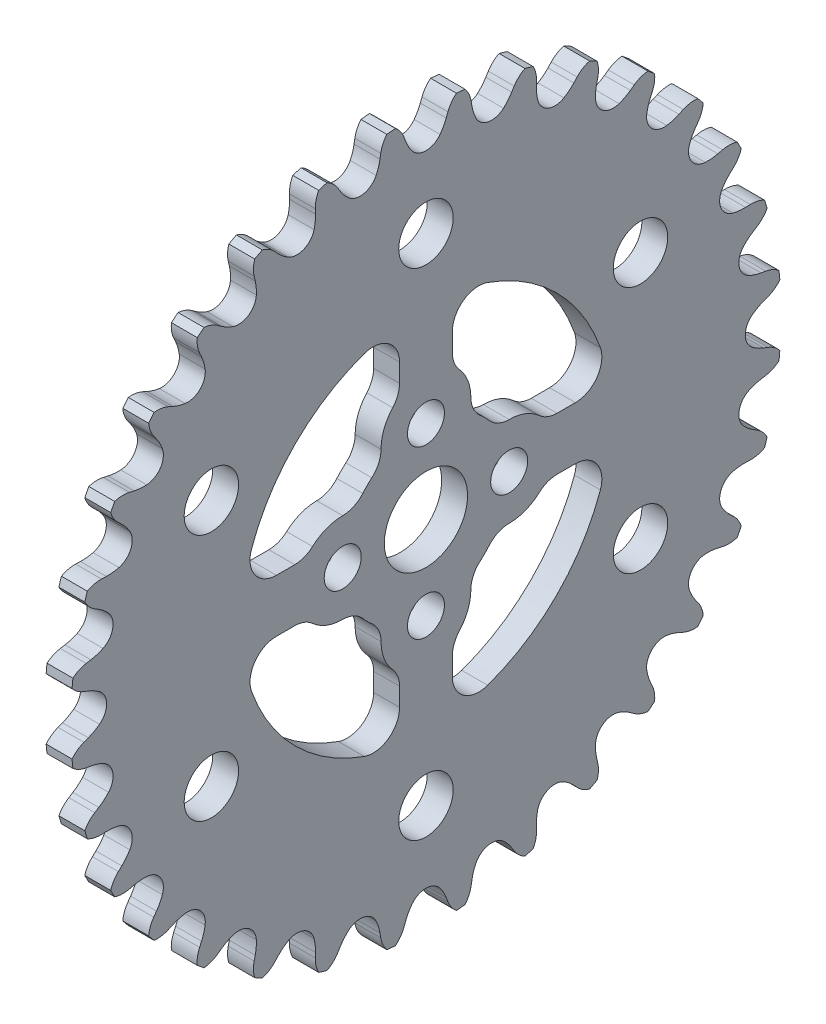
SolidWorks part; units mm, degrees
ref_plane "Front Plane" through (0, 0, 0) normal (0, 0, 1) x (1, 0, 0)
ref_plane "Top Plane" through (0, 0, 0) normal (0, 1, 0) x (1, 0, 0)
ref_plane "Right Plane" through (0, 0, 0) normal (1, 0, 0) x (0, 0, -1)
ref_plane "Plane1" through (2.4892, 0, 0) normal (1, 0, 0) x (0, 0, -1)
sketch "Sketch1" plane through (2.4892, 0, 0) normal (1, 0, 0) x (0, 0, -1)
  line L0 (12.6071, -2.54) -> (14.3684, -2.54)
  line L1 (2.54, -14.3684) -> (2.54, -12.6071)
  line L2 (-14.3684, -2.54) -> (-12.6071, -2.54)
  line L3 (-2.54, -12.6071) -> (-2.54, -14.3684)
  line L4 (-4.3457, 32.6567) -> (-4.4202, 32.2055)
  line L5 (-8.2408, 31.4456) -> (-8.4823, 31.8339)
  line L6 (-10.6332, 31.1814) -> (-10.6183, 30.7244)
  line L7 (-14.2172, 29.2337) -> (-14.5298, 29.5674)
  line L8 (-16.5121, 28.5078) -> (-16.4083, 28.0625)
  line L9 (-19.6472, 25.8983) -> (-20.0189, 26.1647)
  line L10 (-21.7564, 24.7387) -> (-21.5677, 24.3222)
  line L11 (-24.3222, 21.5677) -> (-24.7387, 21.7564)
  line L12 (-26.1647, 20.0189) -> (-25.8983, 19.6472)
  line L13 (-28.0625, 16.4083) -> (-28.5078, 16.5121)
  line L14 (-29.5674, 14.5298) -> (-29.2337, 14.2172)
  line L15 (-30.7244, 10.6183) -> (-31.1814, 10.6332)
  line L16 (-31.8339, 8.4823) -> (-31.4456, 8.2408)
  line L17 (-32.2055, 4.4202) -> (-32.6567, 4.3457)
  line L18 (-32.877, 2.1088) -> (-32.449, 1.9477)
  line L19 (-32.449, -1.9477) -> (-32.877, -2.1088)
  line L20 (-32.6567, -4.3457) -> (-32.2055, -4.4202)
  line L21 (-31.4456, -8.2408) -> (-31.8339, -8.4823)
  line L22 (-31.1814, -10.6332) -> (-30.7244, -10.6183)
  line L23 (-29.2337, -14.2172) -> (-29.5674, -14.5298)
  line L24 (-28.5078, -16.5121) -> (-28.0625, -16.4083)
  line L25 (-25.8983, -19.6472) -> (-26.1647, -20.0189)
  line L26 (-24.7387, -21.7564) -> (-24.3222, -21.5677)
  line L27 (-21.5677, -24.3222) -> (-21.7564, -24.7387)
  line L28 (-20.0189, -26.1647) -> (-19.6472, -25.8983)
  line L29 (-16.4083, -28.0625) -> (-16.5121, -28.5078)
  line L30 (-14.5298, -29.5674) -> (-14.2172, -29.2337)
  line L31 (-10.6183, -30.7244) -> (-10.6332, -31.1814)
  line L32 (-8.4823, -31.8339) -> (-8.2408, -31.4456)
  line L33 (-4.4202, -32.2055) -> (-4.3457, -32.6567)
  line L34 (-2.1088, -32.877) -> (-1.9477, -32.449)
  line L35 (1.9477, -32.449) -> (2.1088, -32.877)
  line L36 (4.3457, -32.6567) -> (4.4202, -32.2055)
  line L37 (8.2408, -31.4456) -> (8.4823, -31.8339)
  line L38 (10.6332, -31.1814) -> (10.6183, -30.7244)
  line L39 (14.2172, -29.2337) -> (14.5298, -29.5674)
  line L40 (16.5121, -28.5078) -> (16.4083, -28.0625)
  line L41 (19.6472, -25.8983) -> (20.0189, -26.1647)
  line L42 (21.7564, -24.7387) -> (21.5677, -24.3222)
  line L43 (24.3222, -21.5677) -> (24.7387, -21.7564)
  line L44 (26.1647, -20.0189) -> (25.8983, -19.6472)
  line L45 (28.0625, -16.4083) -> (28.5078, -16.5121)
  line L46 (29.5674, -14.5298) -> (29.2337, -14.2172)
  line L47 (30.7244, -10.6183) -> (31.1814, -10.6332)
  line L48 (31.8339, -8.4823) -> (31.4456, -8.2408)
  line L49 (32.2055, -4.4202) -> (32.6567, -4.3457)
  line L50 (32.877, -2.1088) -> (32.449, -1.9477)
  line L51 (32.449, 1.9477) -> (32.877, 2.1088)
  line L52 (32.6567, 4.3457) -> (32.2055, 4.4202)
  line L53 (31.4456, 8.2408) -> (31.8339, 8.4823)
  line L54 (31.1814, 10.6332) -> (30.7244, 10.6183)
  line L55 (29.2337, 14.2172) -> (29.5674, 14.5298)
  line L56 (28.5078, 16.5121) -> (28.0625, 16.4083)
  line L57 (25.8983, 19.6472) -> (26.1647, 20.0189)
  line L58 (24.7387, 21.7564) -> (24.3222, 21.5677)
  line L59 (21.5677, 24.3222) -> (21.7564, 24.7387)
  line L60 (20.0189, 26.1647) -> (19.6472, 25.8983)
  line L61 (16.4083, 28.0625) -> (16.5121, 28.5078)
  line L62 (14.5298, 29.5674) -> (14.2172, 29.2337)
  line L63 (10.6183, 30.7244) -> (10.6332, 31.1814)
  line L64 (8.4823, 31.8339) -> (8.2408, 31.4456)
  line L65 (4.4202, 32.2055) -> (4.3457, 32.6567)
  line L66 (2.1088, 32.877) -> (1.9477, 32.449)
  line L67 (-1.9477, 32.449) -> (-2.1088, 32.877)
  line L68 (14.3684, 2.54) -> (12.6071, 2.54)
  line L69 (2.54, 12.6071) -> (2.54, 14.3684)
  line L70 (-12.6071, 2.54) -> (-14.3684, 2.54)
  line L71 (-2.54, 14.3684) -> (-2.54, 12.6071)
  arc A0 (10.9008, -3.1985) -> (12.6071, -2.54) centre (12.6071, -5.08) cw
  arc A1 (14.3684, -2.54) -> (16.7631, -5.9267) centre (14.3684, -5.08) cw
  arc A2 (16.7631, -5.9267) -> (5.9267, -16.7631) centre (0, 0) cw
  arc A3 (5.9267, -16.7631) -> (2.54, -14.3684) centre (5.08, -14.3684) cw
  arc A4 (2.54, -12.6071) -> (3.1985, -10.9008) centre (5.08, -12.6071) cw
  arc A5 (3.1985, -10.9008) -> (4.318, -8.0023) centre (0, -8) ccw
  arc A6 (4.318, -8.0023) -> (5.2053, -6.0749) centre (6.858, -8.0037) cw
  arc A7 (5.2053, -6.0749) -> (6.0749, -5.2053) centre (0, 0) ccw
  arc A8 (6.0749, -5.2053) -> (8.0023, -4.318) centre (8.0037, -6.858) cw
  arc A9 (8.0023, -4.318) -> (10.9008, -3.1985) centre (8, 0) ccw
  arc A10 (-16.7631, -5.9267) -> (-14.3684, -2.54) centre (-14.3684, -5.08) cw
  arc A11 (-12.6071, -2.54) -> (-10.9008, -3.1985) centre (-12.6071, -5.08) cw
  arc A12 (-10.9008, -3.1985) -> (-8.0023, -4.318) centre (-8, 0) ccw
  arc A13 (-8.0023, -4.318) -> (-6.0749, -5.2053) centre (-8.0037, -6.858) cw
  arc A14 (-6.0749, -5.2053) -> (-5.2053, -6.0749) centre (0, 0) ccw
  arc A15 (-5.2053, -6.0749) -> (-4.318, -8.0023) centre (-6.858, -8.0037) cw
  arc A16 (-4.318, -8.0023) -> (-3.1985, -10.9008) centre (0, -8) ccw
  arc A17 (-3.1985, -10.9008) -> (-2.54, -12.6071) centre (-5.08, -12.6071) cw
  arc A18 (-2.54, -14.3684) -> (-5.9267, -16.7631) centre (-5.08, -14.3684) cw
  arc A19 (-5.9267, -16.7631) -> (-16.7631, -5.9267) centre (0, 0) cw
  arc A20 (-4.4202, 32.2055) -> (-4.789, 31.0358) centre (-8.7012, 32.9123) cw
  arc A21 (-4.789, 31.0358) -> (-7.4524, 30.506) centre (-6.3194, 31.7699) cw
  arc A22 (-7.4524, 30.506) -> (-8.2408, 31.4456) centre (-4.5561, 33.7368) cw
  arc A23 (-8.4823, 31.8339) -> (-9.5131, 32.7892) centre (-10.7432, 30.428) ccw
  arc A24 (-9.5131, 32.7892) -> (-10.3068, 32.5484) centre (0, 0) ccw
  arc A25 (-10.3068, 32.5484) -> (-10.6332, 31.1814) centre (-7.9723, 31.2685) ccw
  arc A26 (-10.6183, 30.7244) -> (-10.7518, 29.5052) centre (-14.9549, 30.5824) cw
  arc A27 (-10.7518, 29.5052) -> (-13.2607, 28.466) centre (-12.396, 29.9266) cw
  arc A28 (-13.2607, 28.466) -> (-14.2172, 29.2337) centre (-11.0503, 32.1997) cw
  arc A29 (-14.5298, 29.5674) -> (-15.7272, 30.3032) centre (-16.4729, 27.7474) ccw
  arc A30 (-15.7272, 30.3032) -> (-16.4587, 29.9122) centre (0, 0) ccw
  arc A31 (-16.4587, 29.9122) -> (-16.5121, 28.5078) centre (-13.9192, 29.1124) ccw
  arc A32 (-16.4083, 28.0625) -> (-16.3014, 26.8407) centre (-20.6339, 27.0772) cw
  arc A33 (-16.3014, 26.8407) -> (-18.5593, 25.332) centre (-17.9962, 26.9332) cw
  arc A34 (-18.5593, 25.332) -> (-19.6472, 25.8983) centre (-17.1198, 29.4252) cw
  arc A35 (-20.0189, 26.1647) -> (-21.3369, 26.6527) centre (-21.5697, 24.0005) ccw
  arc A36 (-21.3369, 26.6527) -> (-21.978, 26.1266) centre (0, 0) ccw
  arc A37 (-21.978, 26.1266) -> (-21.7564, 24.7387) centre (-19.3313, 25.8375) ccw
  arc A38 (-21.5677, 24.3222) -> (-21.2245, 23.1447) centre (-25.5199, 22.5315) cw
  arc A39 (-21.2245, 23.1447) -> (-23.1447, 21.2245) centre (-22.9048, 22.9048) cw
  arc A40 (-23.1447, 21.2245) -> (-24.3222, 21.5677) centre (-22.5315, 25.5199) cw
  arc A41 (-24.7387, 21.7564) -> (-26.1266, 21.978) centre (-25.8375, 19.3313) ccw
  arc A42 (-26.1266, 21.978) -> (-26.6527, 21.3369) centre (0, 0) ccw
  arc A43 (-26.6527, 21.3369) -> (-26.1647, 20.0189) centre (-24.0005, 21.5697) ccw
  arc A44 (-25.8983, 19.6472) -> (-25.332, 18.5593) centre (-29.4252, 17.1198) cw
  arc A45 (-25.332, 18.5593) -> (-26.8407, 16.3014) centre (-26.9332, 17.9962) cw
  arc A46 (-26.8407, 16.3014) -> (-28.0625, 16.4083) centre (-27.0772, 20.6339) cw
  arc A47 (-28.5078, 16.5121) -> (-29.9122, 16.4587) centre (-29.1124, 13.9192) ccw
  arc A48 (-29.9122, 16.4587) -> (-30.3032, 15.7272) centre (0, 0) ccw
  arc A49 (-30.3032, 15.7272) -> (-29.5674, 14.5298) centre (-27.7474, 16.4729) ccw
  arc A50 (-29.2337, 14.2172) -> (-28.466, 13.2607) centre (-32.1997, 11.0503) cw
  arc A51 (-28.466, 13.2607) -> (-29.5052, 10.7518) centre (-29.9266, 12.396) cw
  arc A52 (-29.5052, 10.7518) -> (-30.7244, 10.6183) centre (-30.5824, 14.9549) cw
  arc A53 (-31.1814, 10.6332) -> (-32.5484, 10.3068) centre (-31.2685, 7.9723) ccw
  arc A54 (-32.5484, 10.3068) -> (-32.7892, 9.5131) centre (0, 0) ccw
  arc A55 (-32.7892, 9.5131) -> (-31.8339, 8.4823) centre (-30.428, 10.7432) ccw
  arc A56 (-31.4456, 8.2408) -> (-30.506, 7.4524) centre (-33.7368, 4.5561) cw
  arc A57 (-30.506, 7.4524) -> (-31.0358, 4.789) centre (-31.7699, 6.3194) cw
  arc A58 (-31.0358, 4.789) -> (-32.2055, 4.4202) centre (-32.9123, 8.7012) cw
  arc A59 (-32.6567, 4.3457) -> (-33.9338, 3.7589) centre (-32.223, 1.7189) ccw
  arc A60 (-33.9338, 3.7589) -> (-34.0151, 2.9335) centre (0, 0) ccw
  arc A61 (-34.0151, 2.9335) -> (-32.877, 2.1088) centre (-31.9392, 4.6005) ccw
  arc A62 (-32.449, 1.9477) -> (-31.3738, 1.3578) centre (-33.9774, -2.1131) cw
  arc A63 (-31.3738, 1.3578) -> (-31.3738, -1.3578) centre (-32.3923, 0) cw
  arc A64 (-31.3738, -1.3578) -> (-32.449, -1.9477) centre (-33.9774, 2.1131) cw
  arc A65 (-32.877, -2.1088) -> (-34.0151, -2.9335) centre (-31.9392, -4.6005) ccw
  arc A66 (-34.0151, -2.9335) -> (-33.9338, -3.7589) centre (0, 0) ccw
  arc A67 (-33.9338, -3.7589) -> (-32.6567, -4.3457) centre (-32.223, -1.7189) ccw
  arc A68 (-32.2055, -4.4202) -> (-31.0358, -4.789) centre (-32.9123, -8.7012) cw
  arc A69 (-31.0358, -4.789) -> (-30.506, -7.4524) centre (-31.7699, -6.3194) cw
  arc A70 (-30.506, -7.4524) -> (-31.4456, -8.2408) centre (-33.7368, -4.5561) cw
  arc A71 (-31.8339, -8.4823) -> (-32.7892, -9.5131) centre (-30.428, -10.7432) ccw
  arc A72 (-32.7892, -9.5131) -> (-32.5484, -10.3068) centre (0, 0) ccw
  arc A73 (-32.5484, -10.3068) -> (-31.1814, -10.6332) centre (-31.2685, -7.9723) ccw
  arc A74 (-30.7244, -10.6183) -> (-29.5052, -10.7518) centre (-30.5824, -14.9549) cw
  arc A75 (-29.5052, -10.7518) -> (-28.466, -13.2607) centre (-29.9266, -12.396) cw
  arc A76 (-28.466, -13.2607) -> (-29.2337, -14.2172) centre (-32.1997, -11.0503) cw
  arc A77 (-29.5674, -14.5298) -> (-30.3032, -15.7272) centre (-27.7474, -16.4729) ccw
  arc A78 (-30.3032, -15.7272) -> (-29.9122, -16.4587) centre (0, 0) ccw
  arc A79 (-29.9122, -16.4587) -> (-28.5078, -16.5121) centre (-29.1124, -13.9192) ccw
  arc A80 (-28.0625, -16.4083) -> (-26.8407, -16.3014) centre (-27.0772, -20.6339) cw
  arc A81 (-26.8407, -16.3014) -> (-25.332, -18.5593) centre (-26.9332, -17.9962) cw
  arc A82 (-25.332, -18.5593) -> (-25.8983, -19.6472) centre (-29.4252, -17.1198) cw
  arc A83 (-26.1647, -20.0189) -> (-26.6527, -21.3369) centre (-24.0005, -21.5697) ccw
  arc A84 (-26.6527, -21.3369) -> (-26.1266, -21.978) centre (0, 0) ccw
  arc A85 (-26.1266, -21.978) -> (-24.7387, -21.7564) centre (-25.8375, -19.3313) ccw
  arc A86 (-24.3222, -21.5677) -> (-23.1447, -21.2245) centre (-22.5315, -25.5199) cw
  arc A87 (-23.1447, -21.2245) -> (-21.2245, -23.1447) centre (-22.9048, -22.9048) cw
  arc A88 (-21.2245, -23.1447) -> (-21.5677, -24.3222) centre (-25.5199, -22.5315) cw
  arc A89 (-21.7564, -24.7387) -> (-21.978, -26.1266) centre (-19.3313, -25.8375) ccw
  arc A90 (-21.978, -26.1266) -> (-21.3369, -26.6527) centre (0, 0) ccw
  arc A91 (-21.3369, -26.6527) -> (-20.0189, -26.1647) centre (-21.5697, -24.0005) ccw
  arc A92 (-19.6472, -25.8983) -> (-18.5593, -25.332) centre (-17.1198, -29.4252) cw
  arc A93 (-18.5593, -25.332) -> (-16.3014, -26.8407) centre (-17.9962, -26.9332) cw
  arc A94 (-16.3014, -26.8407) -> (-16.4083, -28.0625) centre (-20.6339, -27.0772) cw
  arc A95 (-16.5121, -28.5078) -> (-16.4587, -29.9122) centre (-13.9192, -29.1124) ccw
  arc A96 (-16.4587, -29.9122) -> (-15.7272, -30.3032) centre (0, 0) ccw
  arc A97 (-15.7272, -30.3032) -> (-14.5298, -29.5674) centre (-16.4729, -27.7474) ccw
  arc A98 (-14.2172, -29.2337) -> (-13.2607, -28.466) centre (-11.0503, -32.1997) cw
  arc A99 (-13.2607, -28.466) -> (-10.7518, -29.5052) centre (-12.396, -29.9266) cw
  arc A100 (-10.7518, -29.5052) -> (-10.6183, -30.7244) centre (-14.9549, -30.5824) cw
  arc A101 (-10.6332, -31.1814) -> (-10.3068, -32.5484) centre (-7.9723, -31.2685) ccw
  arc A102 (-10.3068, -32.5484) -> (-9.5131, -32.7892) centre (0, 0) ccw
  arc A103 (-9.5131, -32.7892) -> (-8.4823, -31.8339) centre (-10.7432, -30.428) ccw
  arc A104 (-8.2408, -31.4456) -> (-7.4524, -30.506) centre (-4.5561, -33.7368) cw
  arc A105 (-7.4524, -30.506) -> (-4.789, -31.0358) centre (-6.3194, -31.7699) cw
  arc A106 (-4.789, -31.0358) -> (-4.4202, -32.2055) centre (-8.7012, -32.9123) cw
  arc A107 (-4.3457, -32.6567) -> (-3.7589, -33.9338) centre (-1.7189, -32.223) ccw
  arc A108 (-3.7589, -33.9338) -> (-2.9335, -34.0151) centre (0, 0) ccw
  arc A109 (-2.9335, -34.0151) -> (-2.1088, -32.877) centre (-4.6005, -31.9392) ccw
  arc A110 (-1.9477, -32.449) -> (-1.3578, -31.3738) centre (2.1131, -33.9774) cw
  arc A111 (-1.3578, -31.3738) -> (1.3578, -31.3738) centre (0, -32.3923) cw
  arc A112 (1.3578, -31.3738) -> (1.9477, -32.449) centre (-2.1131, -33.9774) cw
  arc A113 (2.1088, -32.877) -> (2.9335, -34.0151) centre (4.6005, -31.9392) ccw
  arc A114 (2.9335, -34.0151) -> (3.7589, -33.9338) centre (0, 0) ccw
  arc A115 (3.7589, -33.9338) -> (4.3457, -32.6567) centre (1.7189, -32.223) ccw
  arc A116 (4.4202, -32.2055) -> (4.789, -31.0358) centre (8.7012, -32.9123) cw
  arc A117 (4.789, -31.0358) -> (7.4524, -30.506) centre (6.3194, -31.7699) cw
  arc A118 (7.4524, -30.506) -> (8.2408, -31.4456) centre (4.5561, -33.7368) cw
  arc A119 (8.4823, -31.8339) -> (9.5131, -32.7892) centre (10.7432, -30.428) ccw
  arc A120 (9.5131, -32.7892) -> (10.3068, -32.5484) centre (0, 0) ccw
  arc A121 (10.3068, -32.5484) -> (10.6332, -31.1814) centre (7.9723, -31.2685) ccw
  arc A122 (10.6183, -30.7244) -> (10.7518, -29.5052) centre (14.9549, -30.5824) cw
  arc A123 (10.7518, -29.5052) -> (13.2607, -28.466) centre (12.396, -29.9266) cw
  arc A124 (13.2607, -28.466) -> (14.2172, -29.2337) centre (11.0503, -32.1997) cw
  arc A125 (14.5298, -29.5674) -> (15.7272, -30.3032) centre (16.4729, -27.7474) ccw
  arc A126 (15.7272, -30.3032) -> (16.4587, -29.9122) centre (0, 0) ccw
  arc A127 (16.4587, -29.9122) -> (16.5121, -28.5078) centre (13.9192, -29.1124) ccw
  arc A128 (16.4083, -28.0625) -> (16.3014, -26.8407) centre (20.6339, -27.0772) cw
  arc A129 (16.3014, -26.8407) -> (18.5593, -25.332) centre (17.9962, -26.9332) cw
  arc A130 (18.5593, -25.332) -> (19.6472, -25.8983) centre (17.1198, -29.4252) cw
  arc A131 (20.0189, -26.1647) -> (21.3369, -26.6527) centre (21.5697, -24.0005) ccw
  arc A132 (21.3369, -26.6527) -> (21.978, -26.1266) centre (0, 0) ccw
  arc A133 (21.978, -26.1266) -> (21.7564, -24.7387) centre (19.3313, -25.8375) ccw
  arc A134 (21.5677, -24.3222) -> (21.2245, -23.1447) centre (25.5199, -22.5315) cw
  arc A135 (21.2245, -23.1447) -> (23.1447, -21.2245) centre (22.9048, -22.9048) cw
  arc A136 (23.1447, -21.2245) -> (24.3222, -21.5677) centre (22.5315, -25.5199) cw
  arc A137 (24.7387, -21.7564) -> (26.1266, -21.978) centre (25.8375, -19.3313) ccw
  arc A138 (26.1266, -21.978) -> (26.6527, -21.3369) centre (0, 0) ccw
  arc A139 (26.6527, -21.3369) -> (26.1647, -20.0189) centre (24.0005, -21.5697) ccw
  arc A140 (25.8983, -19.6472) -> (25.332, -18.5593) centre (29.4252, -17.1198) cw
  arc A141 (25.332, -18.5593) -> (26.8407, -16.3014) centre (26.9332, -17.9962) cw
  arc A142 (26.8407, -16.3014) -> (28.0625, -16.4083) centre (27.0772, -20.6339) cw
  arc A143 (28.5078, -16.5121) -> (29.9122, -16.4587) centre (29.1124, -13.9192) ccw
  arc A144 (29.9122, -16.4587) -> (30.3032, -15.7272) centre (0, 0) ccw
  arc A145 (30.3032, -15.7272) -> (29.5674, -14.5298) centre (27.7474, -16.4729) ccw
  arc A146 (29.2337, -14.2172) -> (28.466, -13.2607) centre (32.1997, -11.0503) cw
  arc A147 (28.466, -13.2607) -> (29.5052, -10.7518) centre (29.9266, -12.396) cw
  arc A148 (29.5052, -10.7518) -> (30.7244, -10.6183) centre (30.5824, -14.9549) cw
  arc A149 (31.1814, -10.6332) -> (32.5484, -10.3068) centre (31.2685, -7.9723) ccw
  arc A150 (32.5484, -10.3068) -> (32.7892, -9.5131) centre (0, 0) ccw
  arc A151 (32.7892, -9.5131) -> (31.8339, -8.4823) centre (30.428, -10.7432) ccw
  arc A152 (31.4456, -8.2408) -> (30.506, -7.4524) centre (33.7368, -4.5561) cw
  arc A153 (30.506, -7.4524) -> (31.0358, -4.789) centre (31.7699, -6.3194) cw
  arc A154 (31.0358, -4.789) -> (32.2055, -4.4202) centre (32.9123, -8.7012) cw
  arc A155 (32.6567, -4.3457) -> (33.9338, -3.7589) centre (32.223, -1.7189) ccw
  arc A156 (33.9338, -3.7589) -> (34.0151, -2.9335) centre (0, 0) ccw
  arc A157 (34.0151, -2.9335) -> (32.877, -2.1088) centre (31.9392, -4.6005) ccw
  arc A158 (32.449, -1.9477) -> (31.3738, -1.3578) centre (33.9774, 2.1131) cw
  arc A159 (31.3738, -1.3578) -> (31.3738, 1.3578) centre (32.3923, 0) cw
  arc A160 (31.3738, 1.3578) -> (32.449, 1.9477) centre (33.9774, -2.1131) cw
  arc A161 (32.877, 2.1088) -> (34.0151, 2.9335) centre (31.9392, 4.6005) ccw
  arc A162 (34.0151, 2.9335) -> (33.9338, 3.7589) centre (0, 0) ccw
  arc A163 (33.9338, 3.7589) -> (32.6567, 4.3457) centre (32.223, 1.7189) ccw
  arc A164 (32.2055, 4.4202) -> (31.0358, 4.789) centre (32.9123, 8.7012) cw
  arc A165 (31.0358, 4.789) -> (30.506, 7.4524) centre (31.7699, 6.3194) cw
  arc A166 (30.506, 7.4524) -> (31.4456, 8.2408) centre (33.7368, 4.5561) cw
  arc A167 (31.8339, 8.4823) -> (32.7892, 9.5131) centre (30.428, 10.7432) ccw
  arc A168 (32.7892, 9.5131) -> (32.5484, 10.3068) centre (0, 0) ccw
  arc A169 (32.5484, 10.3068) -> (31.1814, 10.6332) centre (31.2685, 7.9723) ccw
  arc A170 (30.7244, 10.6183) -> (29.5052, 10.7518) centre (30.5824, 14.9549) cw
  arc A171 (29.5052, 10.7518) -> (28.466, 13.2607) centre (29.9266, 12.396) cw
  arc A172 (28.466, 13.2607) -> (29.2337, 14.2172) centre (32.1997, 11.0503) cw
  arc A173 (29.5674, 14.5298) -> (30.3032, 15.7272) centre (27.7474, 16.4729) ccw
  arc A174 (30.3032, 15.7272) -> (29.9122, 16.4587) centre (0, 0) ccw
  arc A175 (29.9122, 16.4587) -> (28.5078, 16.5121) centre (29.1124, 13.9192) ccw
  arc A176 (28.0625, 16.4083) -> (26.8407, 16.3014) centre (27.0772, 20.6339) cw
  arc A177 (26.8407, 16.3014) -> (25.332, 18.5593) centre (26.9332, 17.9962) cw
  arc A178 (25.332, 18.5593) -> (25.8983, 19.6472) centre (29.4252, 17.1198) cw
  arc A179 (26.1647, 20.0189) -> (26.6527, 21.3369) centre (24.0005, 21.5697) ccw
  arc A180 (26.6527, 21.3369) -> (26.1266, 21.978) centre (0, 0) ccw
  arc A181 (26.1266, 21.978) -> (24.7387, 21.7564) centre (25.8375, 19.3313) ccw
  arc A182 (24.3222, 21.5677) -> (23.1447, 21.2245) centre (22.5315, 25.5199) cw
  arc A183 (23.1447, 21.2245) -> (21.2245, 23.1447) centre (22.9048, 22.9048) cw
  arc A184 (21.2245, 23.1447) -> (21.5677, 24.3222) centre (25.5199, 22.5315) cw
  arc A185 (21.7564, 24.7387) -> (21.978, 26.1266) centre (19.3313, 25.8375) ccw
  arc A186 (21.978, 26.1266) -> (21.3369, 26.6527) centre (0, 0) ccw
  arc A187 (21.3369, 26.6527) -> (20.0189, 26.1647) centre (21.5697, 24.0005) ccw
  arc A188 (19.6472, 25.8983) -> (18.5593, 25.332) centre (17.1198, 29.4252) cw
  arc A189 (18.5593, 25.332) -> (16.3014, 26.8407) centre (17.9962, 26.9332) cw
  arc A190 (16.3014, 26.8407) -> (16.4083, 28.0625) centre (20.6339, 27.0772) cw
  arc A191 (16.5121, 28.5078) -> (16.4587, 29.9122) centre (13.9192, 29.1124) ccw
  arc A192 (16.4587, 29.9122) -> (15.7272, 30.3032) centre (0, 0) ccw
  arc A193 (15.7272, 30.3032) -> (14.5298, 29.5674) centre (16.4729, 27.7474) ccw
  arc A194 (14.2172, 29.2337) -> (13.2607, 28.466) centre (11.0503, 32.1997) cw
  arc A195 (13.2607, 28.466) -> (10.7518, 29.5052) centre (12.396, 29.9266) cw
  arc A196 (10.7518, 29.5052) -> (10.6183, 30.7244) centre (14.9549, 30.5824) cw
  arc A197 (10.6332, 31.1814) -> (10.3068, 32.5484) centre (7.9723, 31.2685) ccw
  arc A198 (10.3068, 32.5484) -> (9.5131, 32.7892) centre (0, 0) ccw
  arc A199 (9.5131, 32.7892) -> (8.4823, 31.8339) centre (10.7432, 30.428) ccw
  arc A200 (8.2408, 31.4456) -> (7.4524, 30.506) centre (4.5561, 33.7368) cw
  arc A201 (7.4524, 30.506) -> (4.789, 31.0358) centre (6.3194, 31.7699) cw
  arc A202 (4.789, 31.0358) -> (4.4202, 32.2055) centre (8.7012, 32.9123) cw
  arc A203 (4.3457, 32.6567) -> (3.7589, 33.9338) centre (1.7189, 32.223) ccw
  arc A204 (3.7589, 33.9338) -> (2.9335, 34.0151) centre (0, 0) ccw
  arc A205 (2.9335, 34.0151) -> (2.1088, 32.877) centre (4.6005, 31.9392) ccw
  arc A206 (1.9477, 32.449) -> (1.3578, 31.3738) centre (-2.1131, 33.9774) cw
  arc A207 (1.3578, 31.3738) -> (-1.3578, 31.3738) centre (0, 32.3923) cw
  arc A208 (-1.3578, 31.3738) -> (-1.9477, 32.449) centre (2.1131, 33.9774) cw
  arc A209 (-2.1088, 32.877) -> (-2.9335, 34.0151) centre (-4.6005, 31.9392) ccw
  arc A210 (-2.9335, 34.0151) -> (-3.7589, 33.9338) centre (0, 0) ccw
  arc A211 (-3.7589, 33.9338) -> (-4.3457, 32.6567) centre (-1.7189, 32.223) ccw
  circle A212 centre (0, 0) radius 4
  circle A213 centre (0, 8) radius 1.778
  circle A214 centre (8, 0) radius 1.778
  circle A215 centre (0, -8) radius 1.778
  circle A216 centre (-8, 0) radius 1.778
  circle A217 centre (0, 23.8125) radius 2.6162
  circle A218 centre (20.6222, 11.9062) radius 2.6162
  circle A219 centre (20.6222, -11.9062) radius 2.6162
  circle A220 centre (0, -23.8125) radius 2.6162
  circle A221 centre (-20.6222, -11.9062) radius 2.6162
  circle A222 centre (-20.6222, 11.9063) radius 2.6162
  arc A223 (5.9267, 16.7631) -> (16.7631, 5.9267) centre (0, 0) cw
  arc A224 (16.7631, 5.9267) -> (14.3684, 2.54) centre (14.3684, 5.08) cw
  arc A225 (12.6071, 2.54) -> (10.9008, 3.1985) centre (12.6071, 5.08) cw
  arc A226 (10.9008, 3.1985) -> (8.0023, 4.318) centre (8, 0) ccw
  arc A227 (8.0023, 4.318) -> (6.0749, 5.2053) centre (8.0037, 6.858) cw
  arc A228 (6.0749, 5.2053) -> (5.2053, 6.0749) centre (0, 0) ccw
  arc A229 (5.2053, 6.0749) -> (4.318, 8.0023) centre (6.858, 8.0037) cw
  arc A230 (4.318, 8.0023) -> (3.1985, 10.9008) centre (0, 8) ccw
  arc A231 (3.1985, 10.9008) -> (2.54, 12.6071) centre (5.08, 12.6071) cw
  arc A232 (2.54, 14.3684) -> (5.9267, 16.7631) centre (5.08, 14.3684) cw
  arc A233 (-10.9008, 3.1985) -> (-12.6071, 2.54) centre (-12.6071, 5.08) cw
  arc A234 (-14.3684, 2.54) -> (-16.7631, 5.9267) centre (-14.3684, 5.08) cw
  arc A235 (-16.7631, 5.9267) -> (-5.9267, 16.7631) centre (0, 0) cw
  arc A236 (-5.9267, 16.7631) -> (-2.54, 14.3684) centre (-5.08, 14.3684) cw
  arc A237 (-2.54, 12.6071) -> (-3.1985, 10.9008) centre (-5.08, 12.6071) cw
  arc A238 (-3.1985, 10.9008) -> (-4.318, 8.0023) centre (0, 8) ccw
  arc A239 (-4.318, 8.0023) -> (-5.2053, 6.0749) centre (-6.858, 8.0037) cw
  arc A240 (-5.2053, 6.0749) -> (-6.0749, 5.2053) centre (0, 0) ccw
  arc A241 (-6.0749, 5.2053) -> (-8.0023, 4.318) centre (-8.0037, 6.858) cw
  arc A242 (-8.0023, 4.318) -> (-10.9008, 3.1985) centre (-8, 0) ccw
extrude "Boss-Extrude1" add sketch "Sketch1" against normal blind 2.4892
